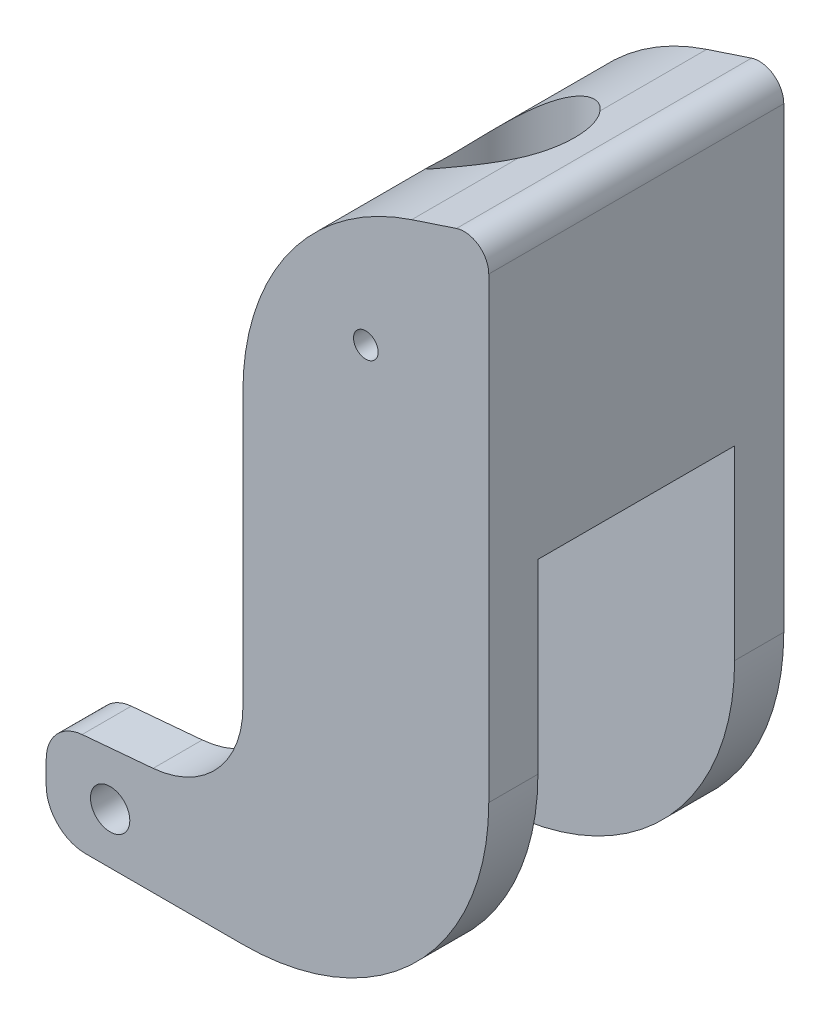
SolidWorks part; units mm, degrees
ref_plane "Front Plane" through (0, 0, 0) normal (0, 0, 1) x (1, 0, 0)
ref_plane "Top Plane" through (0, 0, 0) normal (0, 1, 0) x (1, 0, 0)
ref_plane "Right Plane" through (0, 0, 0) normal (1, 0, 0) x (0, 0, -1)
sketch "Sketch1" plane through (0, 0, 0) normal (0, 0, 1) x (1, 0, 0)
  line L0 (0, 18.3266) -> (0, 73.8482)
  line L1 (-18.2569, -1.5973) -> (-32.6972, -2.8606)
  line L2 (-40, -10.8302) -> (-40, -15.4995)
  line L3 (-32, -23.4995) -> (0, -23.4995)
  line L4 (50, 26.5005) -> (50, 119.5852)
  line L5 (43.4331, 124.3333) -> (34.3307, 121.3295)
  arc A0 (0, 73.8482) -> (34.3307, 121.3295) centre (50, 73.8482) cw
  arc A1 (0, -23.4995) -> (50, 26.5005) centre (0, 26.5005) ccw
  arc A2 (50, 119.5852) -> (43.4331, 124.3333) centre (45, 119.5852) ccw
  arc A3 (-32.6972, -2.8606) -> (-40, -10.8302) centre (-32, -10.8302) ccw
  arc A4 (-40, -15.4995) -> (-32, -23.4995) centre (-32, -15.4995) ccw
  arc A5 (0, 18.3266) -> (-18.2569, -1.5973) centre (-20, 18.3266) cw
  circle A6 centre (-27, -13.1649) radius 4
  point P9 (0, 110)
  point P12 (50, -23.4995)
  point P15 (50, 126.5005)
  point P18 (-40, -3.4995)
  point P21 (-40, -23.4995)
  point P24 (0, 0)
  point P28 (-40, -13.1649)
  dimension "D7" = 50
  dimension "D8" = 50
  dimension "D9" = 5
  dimension "D10" = 8
  dimension "D11" = 20
  dimension "D12" = 8
  dimension "D1" = 110
  dimension "D2" = 95
  dimension "D3" = 40
  dimension "D4" = 90
  dimension "D5" = 150
  dimension "D6" = 20
  dimension "D13" = 13
extrude "Boss-Extrude1" add sketch "Sketch1" along normal blind 60
sketch "Sketch2" plane through (0, 0, 0) normal (1, 0, 0) x (0, 0, -1)
  line L0 (-60, 124.3333) -> (0, 124.3333) construction
  line L1 (-10, -35.6667) -> (-50, -35.6667)
  line L2 (-10, -35.6667) -> (-10, 64.3333)
  line L3 (-10, 64.3333) -> (-50, 64.3333)
  line L4 (-50, -35.6667) -> (-50, 64.3333)
  line L5 (-10, -35.6667) -> (-50, 64.3333) construction
  line L6 (-10, 64.3333) -> (-50, -35.6667) construction
  line L7 (-60, 73.8482) -> (-60, 18.3266) construction
  line L8 (0, 73.8482) -> (0, 18.3266) construction
  point P0 (-30, 14.3333)
  dimension "D1" = 60
  dimension "D2" = 10
  dimension "D3" = 10
  dimension "D4" = 100
extrude "Cut-Extrude1" cut sketch "Sketch2" against normal through all both and the other way through all
sketch "Sketch4" plane through (0, 0, 0) normal (0, 1, 0) x (1, 0, 0)
  line L0 (50, -60) -> (50, 0) construction
  line L1 (50, -60) -> (50, 0) construction
  circle A0 centre (25, -30) radius 12.5
  dimension "D2" = 25
  dimension "D1" = 25
  dimension "D3" = 30
extrude "Cut-Extrude2" cut sketch "Sketch4" against normal through all both and the other way through all
sketch "Sketch5" plane through (0, 0, 60) normal (0, 0, 1) x (1, 0, 0)
  line L6 (0, 73.8482) -> (0, 18.3266)
  line L7 (-18.2569, -1.5973) -> (-32.6972, -2.8606)
  line L8 (-40, -10.8302) -> (-40, -15.4995)
  line L9 (-32, -23.4995) -> (0, -23.4995)
  line L10 (50, 26.5005) -> (50, 119.5852)
  line L11 (43.4331, 124.3333) -> (34.3307, 121.3295)
  line L12 (0, 73.8482) -> (0, 18.3266) construction
  line L13 (-18.2569, -1.5973) -> (-32.6972, -2.8606) construction
  line L14 (-40, -10.8302) -> (-40, -15.4995) construction
  line L15 (-32, -23.4995) -> (0, -23.4995) construction
  line L16 (50, 26.5005) -> (50, 119.5852) construction
  line L17 (43.4331, 124.3333) -> (34.3307, 121.3295) construction
  circle A0 centre (25, 94.5852) radius 2.5
  arc A6 (34.3307, 121.3295) -> (0, 73.8482) centre (50, 73.8482) ccw
  arc A7 (-18.2569, -1.5973) -> (0, 18.3266) centre (-20, 18.3266) ccw
  arc A8 (-32.6972, -2.8606) -> (-40, -10.8302) centre (-32, -10.8302) ccw
  arc A9 (-40, -15.4995) -> (-32, -23.4995) centre (-32, -15.4995) ccw
  arc A10 (0, -23.4995) -> (50, 26.5005) centre (0, 26.5005) ccw
  arc A11 (50, 119.5852) -> (43.4331, 124.3333) centre (45, 119.5852) ccw
  arc A12 (34.3307, 121.3295) -> (0, 73.8482) centre (50, 73.8482) ccw construction
  arc A13 (-18.2569, -1.5973) -> (0, 18.3266) centre (-20, 18.3266) ccw construction
  arc A14 (-32.6972, -2.8606) -> (-40, -10.8302) centre (-32, -10.8302) ccw construction
  arc A15 (-40, -15.4995) -> (-32, -23.4995) centre (-32, -15.4995) ccw construction
  arc A16 (0, -23.4995) -> (50, 26.5005) centre (0, 26.5005) ccw construction
  arc A17 (50, 119.5852) -> (43.4331, 124.3333) centre (45, 119.5852) ccw construction
  dimension "D4" = 5
  dimension "D2" = 25
  dimension "D3" = 25
  dimension "D1" = 0
extrude "Cut-Extrude3" cut sketch "Sketch5" against normal through all both
